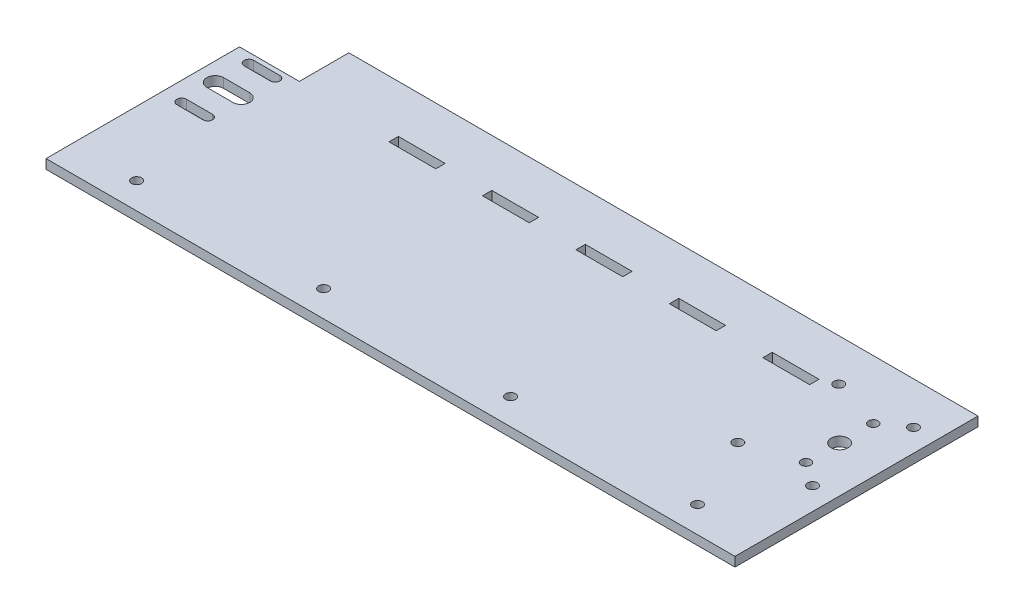
SolidWorks part; units mm, degrees
ref_plane "Front Plane" through (0, 0, 0) normal (0, 0, 1) x (1, 0, 0)
ref_plane "Top Plane" through (0, 0, 0) normal (0, 1, 0) x (1, 0, 0)
ref_plane "Right Plane" through (0, 0, 0) normal (1, 0, 0) x (0, 0, -1)
sketch "Sketch1" plane through (0, 0, 0) normal (0, 1, 0) x (1, 0, 0)
  line L0 (0, 0) -> (0, 40)
  line L3 (0, 40) -> (0, 65)
  line L5 (0, 0) -> (0, -65)
  line L6 (0, -65) -> (-368.537, -65)
  line L11 (-358.537, 20) -> (-344.537, 20)
  line L12 (-344.5, 0.05) -> (-358.5, 0.05)
  line L15 (-134.5556, 39.5) -> (-109.5556, 39.5)
  line L17 (-344.5, -5.05) -> (-358.5, -5.05)
  line L19 (-134.5556, 34.5) -> (-109.5556, 34.5)
  line L21 (-358.537, 11) -> (-344.537, 11)
  line L22 (0, 65) -> (-336.537, 65)
  line L23 (-358.5, 36.05) -> (-344.5, 36.05)
  line L24 (-84.5556, 39.5) -> (-59.5556, 39.5)
  line L25 (-358.5, 30.95) -> (-344.5, 30.95)
  line L28 (-84.5556, 39.5) -> (-59.5556, 39.5)
  line L29 (-84.5556, 39.5) -> (-84.5556, 34.5)
  line L30 (-284.5556, 34.5) -> (-284.5556, 39.5)
  line L31 (-84.5556, 34.5) -> (-59.5556, 34.5)
  line L32 (-259.5556, 39.5) -> (-259.5556, 34.5)
  line L33 (-59.5556, 34.5) -> (-59.5556, 39.5)
  line L34 (-234.5556, 34.5) -> (-234.5556, 39.5)
  line L36 (-209.5556, 39.5) -> (-209.5556, 34.5)
  line L38 (-184.5556, 34.5) -> (-184.5556, 39.5)
  line L41 (-368.537, 38.5) -> (-368.537, -65)
  line L43 (-159.5556, 39.5) -> (-159.5556, 34.5)
  line L45 (-134.5556, 34.5) -> (-134.5556, 39.5)
  line L47 (-109.5556, 39.5) -> (-109.5556, 34.5)
  line L50 (-368.537, 38.5) -> (-336.537, 38.5)
  line L51 (-336.537, 38.5) -> (-336.537, 65)
  line L52 (-368.537, -65) -> (-334.037, -65)
  line L54 (-284.5556, 34.5) -> (-259.5556, 34.5)
  line L55 (-284.5556, 39.5) -> (-284.5556, 34.5)
  line L56 (-259.5556, 34.5) -> (-259.5556, 39.5)
  line L57 (-284.5556, 39.5) -> (-259.5556, 39.5)
  line L58 (-234.5556, 39.5) -> (-209.5556, 39.5)
  line L59 (-234.5556, 34.5) -> (-209.5556, 34.5)
  line L60 (-184.5556, 39.5) -> (-159.5556, 39.5)
  line L61 (-184.5556, 34.5) -> (-159.5556, 34.5)
  circle A0 centre (-12, 42.5) radius 2.65
  circle A1 centre (-24.537, 33.5084) radius 2.55
  circle A2 centre (-24.537, -2.4916) radius 2.55
  circle A3 centre (-24.537, 15.5084) radius 4.5
  circle A5 centre (-12, -11.5) radius 2.65
  circle A7 centre (-334.037, -51) radius 2.65
  circle A8 centre (-234.037, -51) radius 2.65
  circle A9 centre (-134.037, -51) radius 2.65
  circle A10 centre (-34.037, -51) radius 2.65
  circle A15 centre (-52, -11.5) radius 2.65
  circle A16 centre (-52, 42.5) radius 2.65
  arc A18 (-344.5, 30.95) -> (-344.5, 36.05) centre (-344.5, 33.5) ccw
  arc A19 (-344.5, -5.05) -> (-344.5, 0.05) centre (-344.5, -2.5) ccw
  arc A20 (-344.537, 11) -> (-344.537, 20) centre (-344.537, 15.5) ccw
  arc A22 (-358.537, 20) -> (-358.537, 11) centre (-358.537, 15.5) ccw
  arc A23 (-358.5, 0.05) -> (-358.5, -5.05) centre (-358.5, -2.5) ccw
  arc A24 (-358.5, 36.05) -> (-358.5, 30.95) centre (-358.5, 33.5) ccw
  dimension "D4" = 18
  dimension "D6" = 5.1
  dimension "D9" = 5.1
  dimension "D13" = 65
  dimension "D19" = 368.537
  dimension "D20" = 14
  dimension "D21" = 5
  dimension "D24" = 5
  dimension "D25" = 25
  dimension "D26" = 25
  dimension "D30" = 40
  dimension "D14" = 5.3
  dimension "D28" = 25
  dimension "D40" = 5.3
  dimension "D5" = 18
  dimension "D10" = 25
  dimension "D11" = 40
  dimension "D18" = 25
  dimension "D22" = 25
  dimension "D23" = 25
  dimension "D27" = 25
  dimension "D29" = 25
  dimension "D32" = 32
  dimension "D35" = 34.5
  dimension "D41" = 100
  dimension "D42" = 100
  dimension "D43" = 100
extrude "Boss-Extrude1" add sketch "Sketch1" along normal blind 5 contours L51 L50 L41 L6 L5 L0 L3 L22 A24 L23 A18 L25 A23 L12 A19 L17 A22 L11 A20 L21 A5 A3 A2 A1 A0 L61 L38 L60 L43 L59 L34 L58 L36 L33 L31 L29 L24 L15
